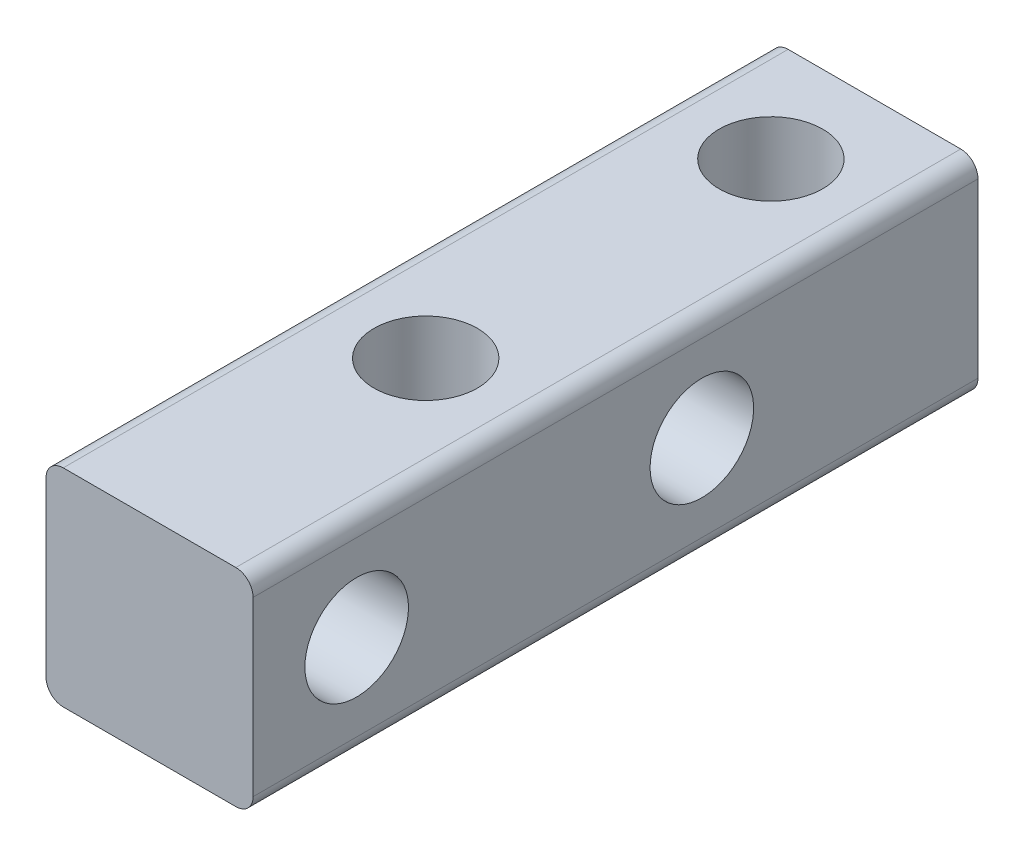
SolidWorks part; units mm, degrees
ref_plane "前视基准面" through (0, 0, 0) normal (0, 0, 1) x (1, 0, 0)
ref_plane "上视基准面" through (0, 0, 0) normal (0, 1, 0) x (1, 0, 0)
ref_plane "右视基准面" through (0, 0, 0) normal (1, 0, 0) x (0, 0, -1)
other "Configuration Table"
sketch "草图1" plane through (0, 0, 0) normal (0, 0, 1) x (1, 0, 0)
  line L1 (-3, -3) -> (3, -3)
  line L2 (-3, -3) -> (-3, 3)
  line L3 (-3, 3) -> (3, 3)
  line L4 (3, -3) -> (3, 3)
  line L5 (-3, -3) -> (3, 3) construction
  line L6 (-3, 3) -> (3, -3) construction
  point P0 (0, 0)
  dimension "D1" = 6
  dimension "D2" = 6
extrude "凸台-拉伸1" add sketch "草图1" along normal blind 21
sketch "草图3" plane through (0, 0, 0) normal (0, 1, 0) x (1, 0, 0)
  circle A0 centre (0, -3) radius 1.5
  circle A1 centre (0, -13) radius 1.5
  dimension "D1" = 3
  dimension "D2" = 3
  dimension "D3" = 10
  dimension "D4" = 3
extrude "切除-拉伸1" cut sketch "草图3" against normal blind 21 and the other way blind 21
sketch "草图4" plane through (0, 0, 0) normal (1, 0, 0) x (0, 0, -1)
  line L0 (-21, 0) -> (0, 0) construction
  line L1 (-21, -3) -> (-21, 3) construction
  line L2 (0, -3) -> (0, 3) construction
  circle A0 centre (-18, 0) radius 1.5
  circle A1 centre (-8, 0) radius 1.5
  dimension "D1" = 3
  dimension "D2" = 3
  dimension "D3" = 10
  dimension "D4" = 3
extrude "切除-拉伸2" cut sketch "草图4" against normal blind 21 and the other way blind 21
fillet "圆角1" radius 0.5 4 edges at (3, -3, 10.5) (-3, -3, 10.5) (-3, 3, 10.5) (3, 3, 10.5)
